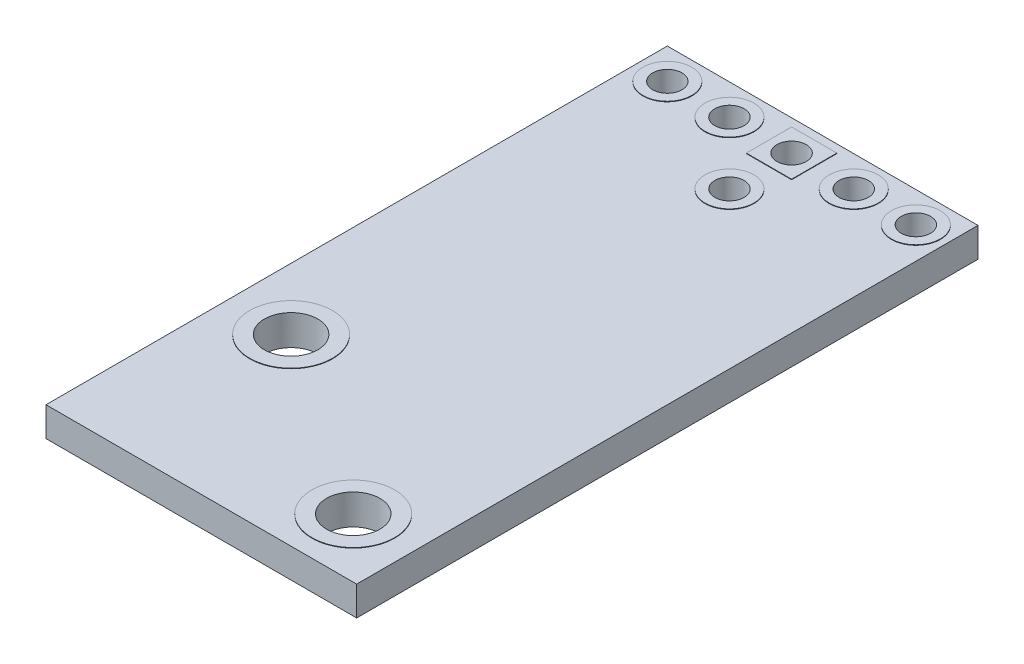
SolidWorks part; units mm, degrees
ref_plane "Plan de face" through (0, 0, 0) normal (0, 0, 1) x (1, 0, 0)
ref_plane "Plan de dessus" through (0, 0, 0) normal (0, 1, 0) x (1, 0, 0)
ref_plane "Plan de droite" through (0, 0, 0) normal (1, 0, 0) x (0, 0, -1)
sketch "Esquisse1" plane through (0, 0, 0) normal (0, 1, 0) x (1, 0, 0)
  line L1 (0, 0) -> (12.7, 0)
  line L2 (0, 0) -> (0, 25.4)
  line L3 (0, 25.4) -> (12.7, 25.4)
  line L4 (12.7, 0) -> (12.7, 25.4)
  dimension "D1" = 25.4
  dimension "D2" = 12.7
extrude "Boss.-Extru.1" add sketch "Esquisse1" along normal blind 1.2
sketch "Esquisse2" plane through (0, 1.2, 0) normal (0, 1, 0) x (1, 0, 0)
  line L0 (2.54, 30.2989) -> (2.54, -15.6653) construction
  line L1 (10.16, 30.2989) -> (10.16, -7.2178) construction
  line L2 (0, 25.4) -> (0, 0) construction
  line L3 (12.7, 0) -> (12.7, 25.4) construction
  line L4 (-2.5944, 2.4) -> (15.2116, 2.4) construction
  line L5 (0, 0) -> (12.7, 0) construction
  line L6 (-3.671, 7.48) -> (18.2758, 7.48) construction
  line L7 (0, 24.13) -> (12.7, 24.13) construction
  line L8 (12.7, 25.4) -> (0, 25.4) construction
  circle A0 centre (2.54, 7.48) radius 1.0922
  circle A1 centre (10.16, 2.4) radius 1.0922
  circle A2 centre (6.35, 24.13) radius 0.6
  circle A3 centre (8.89, 24.13) radius 0.6
  circle A4 centre (11.43, 24.13) radius 0.6
  circle A5 centre (3.81, 24.13) radius 0.6
  circle A6 centre (1.27, 24.13) radius 0.6
  circle A7 centre (6.35, 21.59) radius 0.6
  circle A8 centre (8.89, 21.59) radius 0.6 [skipped]
  circle A9 centre (11.43, 21.59) radius 0.6 [skipped]
  dimension "D6" = 2.1844
  dimension "D7" = 2.1844
  dimension "D8" = 1.2
  dimension "D1" = 7.62
  dimension "D2" = 2.54
  dimension "D3" = 2.54
  dimension "D4" = 2.4
  dimension "D5" = 5.08
  dimension "D11" = 1.27
  dimension "D9" = 3
  dimension "D10" = 2
  dimension "D12" = 3
extrude "Enlèv. mat.-Extru.1" cut sketch "Esquisse2" against normal through all
sketch "Esquisse3" plane through (0, 1.2, 0) normal (0, 1, 0) x (1, 0, 0)
  line L1 (5.425, 25.055) -> (7.275, 25.055)
  line L2 (5.425, 25.055) -> (5.425, 23.205)
  line L3 (5.425, 23.205) -> (7.275, 23.205)
  line L4 (7.275, 25.055) -> (7.275, 23.205)
  line L5 (5.425, 25.055) -> (7.275, 23.205) construction
  line L6 (5.425, 23.205) -> (7.275, 25.055) construction
  circle A0 centre (1.27, 24.13) radius 1
  circle A1 centre (3.81, 24.13) radius 1
  circle A2 centre (1.27, 24.13) radius 0.6
  circle A3 centre (8.89, 24.13) radius 1
  circle A4 centre (11.43, 24.13) radius 1
  circle A5 centre (6.35, 21.59) radius 1
  circle A6 centre (2.54, 7.48) radius 1.6922
  circle A7 centre (10.16, 2.4) radius 1.6922
  circle A8 centre (1.27, 24.13) radius 0.6 construction
  circle A9 centre (3.81, 24.13) radius 0.6 construction
  circle A10 centre (8.89, 24.13) radius 0.6 construction
  circle A11 centre (11.43, 24.13) radius 0.6 construction
  circle A12 centre (6.35, 21.59) radius 0.6 construction
  circle A13 centre (10.16, 2.4) radius 1.0922 construction
  circle A14 centre (2.54, 7.48) radius 1.0922 construction
  circle A15 centre (3.81, 24.13) radius 0.6
  circle A16 centre (6.35, 24.13) radius 0.6
  circle A17 centre (8.89, 24.13) radius 0.6
  circle A18 centre (11.43, 24.13) radius 0.6
  circle A19 centre (6.35, 21.59) radius 0.6
  circle A20 centre (10.16, 2.4) radius 1.0922
  circle A21 centre (2.54, 7.48) radius 1.0922
  point P6 (6.35, 24.13)
  dimension "D1" = 0.4
  dimension "D2" = 0.4
  dimension "D3" = 0.4
  dimension "D4" = 0.4
  dimension "D5" = 0.4
  dimension "D6" = 0.6
  dimension "D7" = 0.6
  dimension "D8" = 1.85
  dimension "D9" = 1.85
extrude "Boss.-Extru.2" add sketch "Esquisse3" along normal blind 0.02
sketch "Esquisse4" plane through (0, 0, 0) normal (0, -1, 0) x (-1, 0, 0)
  line L1 (-5.45, 25.0305) -> (-7.25, 25.0305)
  line L2 (-5.45, 25.0305) -> (-5.45, 23.2295)
  line L3 (-5.45, 23.2295) -> (-7.25, 23.2295)
  line L4 (-7.25, 25.0305) -> (-7.25, 23.2295)
  line L5 (-5.45, 25.0305) -> (-7.25, 23.2295) construction
  line L6 (-5.45, 23.2295) -> (-7.25, 25.0305) construction
  circle A0 centre (-2.54, 7.48) radius 1.6922
  circle A1 centre (-10.16, 2.4) radius 1.6922
  circle A2 centre (-6.35, 21.59) radius 1
  circle A3 centre (-8.89, 24.13) radius 1
  circle A4 centre (-11.43, 24.13) radius 1
  circle A5 centre (-3.81, 24.13) radius 1
  circle A6 centre (-1.27, 24.13) radius 1
  circle A7 centre (-1.27, 24.13) radius 0.6 construction
  circle A8 centre (-3.81, 24.13) radius 0.6 construction
  circle A9 centre (-8.89, 24.13) radius 0.6 construction
  circle A10 centre (-11.43, 24.13) radius 0.6 construction
  circle A11 centre (-6.35, 21.59) radius 0.6 construction
  circle A12 centre (-2.54, 7.48) radius 1.0922 construction
  circle A13 centre (-10.16, 2.4) radius 1.0922 construction
  circle A14 centre (-2.54, 7.48) radius 1.0922
  circle A15 centre (-10.16, 2.4) radius 1.0922
  circle A16 centre (-6.35, 21.59) radius 0.6
  circle A17 centre (-8.89, 24.13) radius 0.6
  circle A18 centre (-11.43, 24.13) radius 0.6
  circle A19 centre (-6.35, 24.13) radius 0.6
  circle A20 centre (-3.81, 24.13) radius 0.6
  circle A21 centre (-1.27, 24.13) radius 0.6
  point P21 (-6.35, 24.13)
  dimension "D3" = 0.4
  dimension "D4" = 0.4
  dimension "D5" = 0.4
  dimension "D6" = 0.4
  dimension "D7" = 0.4
  dimension "D8" = 0.6
  dimension "D1" = 1.8011
  dimension "D2" = 1.8
  dimension ".6" = 0.6
extrude "Boss.-Extru.3" add sketch "Esquisse4" along normal blind 0.02
sketch "Esquisse5" plane through (0, 0, 0) normal (0, -1, 0) x (1, 0, 0)
  line L1 (3.3513, -1.3662) -> (5.8605, -1.3662)
  line L2 (3.3513, -1.3662) -> (3.3513, -3.8817)
  line L3 (3.3513, -3.8817) -> (5.8605, -3.8817)
  line L4 (5.8605, -1.3662) -> (5.8605, -3.8817)
  line L5 (5.5961, -9.3388) -> (8.6875, -9.3388)
  line L6 (5.5961, -9.3388) -> (5.5961, -6.2901)
  line L7 (5.5961, -6.2901) -> (8.6875, -6.2901)
  line L8 (8.6875, -9.3388) -> (8.6875, -6.2901)
  line L9 (8.1055, -14.1372) -> (11.1665, -14.1372)
  line L10 (8.1055, -14.1372) -> (8.1055, -17.2058)
  line L11 (8.1055, -17.2058) -> (11.1665, -17.2058)
  line L12 (11.1665, -14.1372) -> (11.1665, -17.2058)
  line L13 (1.59, -13.4142) -> (2.7836, -13.4142)
  line L14 (1.59, -13.4142) -> (1.59, -16.2685)
  line L15 (1.59, -16.2685) -> (2.7836, -16.2685)
  line L16 (2.7836, -13.4142) -> (2.7836, -16.2685)
  line L17 (1.8599, -16.7459) -> (3.1234, -16.7459)
  line L18 (1.8599, -16.7459) -> (1.8599, -19.599)
  line L19 (1.8599, -19.599) -> (3.1234, -19.599)
  line L20 (3.1234, -16.7459) -> (3.1234, -19.599)
  line L21 (9.2419, -19.7146) -> (10.8325, -19.7146)
  line L22 (9.2419, -19.7146) -> (9.2419, -22.6347)
  line L23 (9.2419, -22.6347) -> (10.8325, -22.6347)
  line L24 (10.8325, -19.7146) -> (10.8325, -22.6347)
extrude "Boss.-Extru.4" add sketch "Esquisse5" along normal blind 0.8
sketch "Esquisse6" plane through (0, 0, 0) normal (0, -1, 0) x (1, 0, 0)
  line L0 (0.7266, -2.0665) -> (1.4605, -2.0665)
  line L1 (0.7266, -2.0665) -> (0.7535, -3.5521)
  line L2 (1.4605, -2.0665) -> (1.4873, -3.5521)
  line L3 (0.7535, -3.5521) -> (1.4873, -3.5521)
  line L4 (11.0867, -7.0264) -> (11.8003, -7.0264)
  line L5 (11.0867, -7.0264) -> (11.164, -8.5548)
  line L6 (11.8003, -7.0264) -> (11.8776, -8.5548)
  line L7 (11.164, -8.5548) -> (11.8776, -8.5548)
  line L8 (11.1253, -10.6273) -> (11.8832, -10.6273)
  line L9 (11.1253, -10.6273) -> (11.1198, -12.1126)
  line L10 (11.8832, -10.6273) -> (11.8776, -12.1126)
  line L11 (11.1198, -12.1126) -> (11.8776, -12.1126)
  line L12 (8.2722, -10.0855) -> (8.2722, -10.8195)
  line L13 (8.2722, -10.0855) -> (9.7751, -10.138)
  line L14 (8.2722, -10.8195) -> (9.7751, -10.8719)
  line L15 (9.7751, -10.138) -> (9.7751, -10.8719)
  line L16 (8.2152, -11.6822) -> (8.2152, -12.4555)
  line L17 (8.2152, -11.6822) -> (9.7751, -11.6878)
  line L18 (8.2152, -12.4555) -> (9.7751, -12.4611)
  line L19 (9.7751, -11.6878) -> (9.7751, -12.4611)
  line L20 (0.7535, -12.0689) -> (1.4873, -12.0689)
  line L21 (0.7535, -12.0689) -> (0.7526, -10.5709)
  line L22 (1.4873, -12.0689) -> (1.4864, -10.5709)
  line L23 (0.7526, -10.5709) -> (1.4864, -10.5709)
  line L24 (2.9363, -12.1256) -> (2.0443, -12.1256)
  line L25 (2.9363, -12.1256) -> (2.9573, -10.5261)
  line L26 (2.0443, -12.1256) -> (2.0653, -10.5261)
  line L27 (2.9573, -10.5261) -> (2.0653, -10.5261)
  line L28 (3.5044, -12.1256) -> (4.2758, -12.1256)
  line L29 (3.5044, -12.1256) -> (3.4733, -10.5799)
  line L30 (4.2758, -12.1256) -> (4.2447, -10.5799)
  line L31 (3.4733, -10.5799) -> (4.2447, -10.5799)
  line L32 (4.993, -12.1748) -> (5.7644, -12.1748)
  line L33 (4.993, -12.1748) -> (4.9619, -10.6292)
  line L34 (5.7644, -12.1748) -> (5.7333, -10.6292)
  line L35 (4.9619, -10.6292) -> (5.7333, -10.6292)
  line L36 (3.726, -22.1426) -> (4.4975, -22.1426)
  line L37 (3.726, -22.1426) -> (3.695, -20.597)
  line L38 (4.4975, -22.1426) -> (4.4664, -20.597)
  line L39 (3.695, -20.597) -> (4.4664, -20.597)
  line L40 (4.934, -18.6695) -> (6.5522, -18.6695)
  line L41 (4.934, -18.6695) -> (4.934, -19.5278)
  line L42 (6.5522, -18.6695) -> (6.5522, -19.5278)
  line L43 (4.934, -19.5278) -> (6.5522, -19.5278)
  line L44 (9.7428, -18.9385) -> (11.2931, -18.9385)
  line L45 (9.7428, -18.9385) -> (9.7428, -18.1917)
  line L46 (11.2931, -18.9385) -> (11.2931, -18.1917)
  line L47 (9.7428, -18.1917) -> (11.2931, -18.1917)
extrude "Boss.-Extru.5" add sketch "Esquisse6" along normal blind 0.6
sketch "Esquisse7" plane through (0, 0, 0) normal (0, -1, 0) x (1, 0, 0)
  line L0 (4.9824, -13.2719) -> (4.9824, -14.0576)
  line L1 (4.9824, -13.2719) -> (6.5241, -13.2549)
  line L2 (4.9824, -14.0576) -> (6.5241, -14.0406)
  line L3 (6.5241, -13.2549) -> (6.5241, -14.0406)
  line L4 (5.0575, -15.7336) -> (6.5983, -15.7336)
  line L5 (5.0575, -15.7336) -> (5.0394, -14.9752)
  line L6 (6.5983, -15.7336) -> (6.5802, -14.9752)
  line L7 (5.0394, -14.9752) -> (6.5802, -14.9752)
  line L8 (5.0484, -17.0261) -> (5.0484, -17.8036)
  line L9 (5.0484, -17.0261) -> (6.5819, -17.0011)
  line L10 (5.0484, -17.8036) -> (6.5819, -17.7786)
  line L11 (6.5819, -17.0011) -> (6.5819, -17.7786)
  line L12 (1.1797, -20.1423) -> (1.1797, -20.9206)
  line L13 (1.1797, -20.1423) -> (2.727, -20.1454)
  line L14 (1.1797, -20.9206) -> (2.727, -20.9237)
  line L15 (2.727, -20.1454) -> (2.727, -20.9237)
  line L16 (1.1347, -22.5063) -> (1.1223, -21.7432)
  line L17 (1.1347, -22.5063) -> (2.702, -22.4847)
  line L18 (1.1223, -21.7432) -> (2.6895, -21.7216)
  line L19 (2.702, -22.4847) -> (2.6895, -21.7216)
extrude "Boss.-Extru.6" add sketch "Esquisse7" along normal blind 0.35
equation "\"Pol_sym\"=2.54"
equation "\"D2@Esquisse2\"=\"Pol_sym\""
